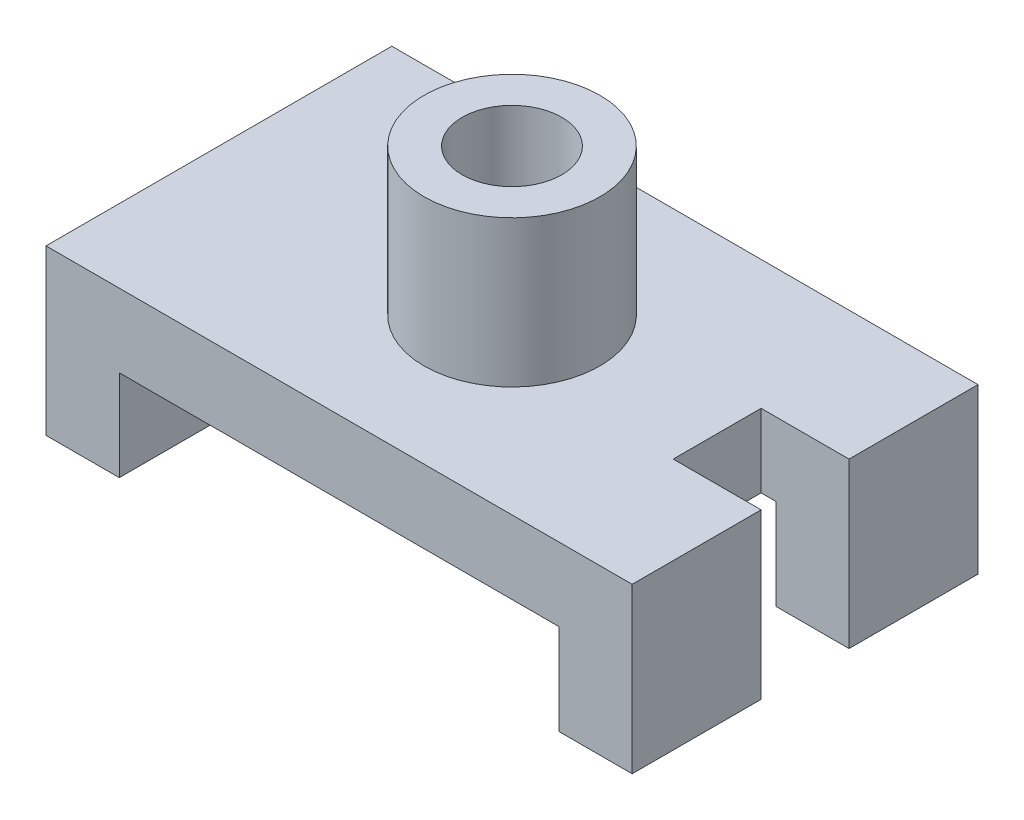
SolidWorks part; units mm, degrees
ref_plane "Alzado" through (0, 0, 0) normal (0, 0, 1) x (1, 0, 0)
ref_plane "Planta" through (0, 0, 0) normal (0, 1, 0) x (1, 0, 0)
ref_plane "Vista lateral" through (0, 0, 0) normal (1, 0, 0) x (0, 0, -1)
sketch "Croquis1" plane through (0, 0, 0) normal (0, 0, 1) x (1, 0, 0)
  line L0 (-3.5, 0) -> (-4, 0)
  line L1 (0, 0) -> (-0.5, 0)
  line L2 (0, 0) -> (0, 1.12)
  line L3 (0, 1.12) -> (-4, 1.12)
  line L4 (-4, 0) -> (-4, 1.12)
  line L6 (-3.5, 0) -> (-3.5, 0.62)
  line L7 (-3.5, 0.62) -> (-0.5, 0.62)
  line L8 (-0.5, 0) -> (-0.5, 0.62)
  dimension "D1" = 3
  dimension "D2" = 4
  dimension "D3" = 1.12
  dimension "D4" = 0.5
extrude "Saliente-Extruir2" add sketch "Croquis1" along normal mid plane 2.36
sketch "Croquis2" plane through (0, 1.12, 0) normal (0, 1, 0) x (1, 0, 0)
  line L0 (0, -1.18) -> (0, 1.18) construction
  line L1 (0, 0.3) -> (-0.6, 0.3)
  line L2 (0, 0.3) -> (0, -0.3)
  line L3 (0, -0.3) -> (-0.6, -0.3)
  line L4 (-0.6, 0.3) -> (-0.6, -0.3)
  line L5 (0, 1.18) -> (-4, 1.18) construction
  dimension "D1" = 0.6
  dimension "D2" = 0.6
  dimension "D3" = 0.88
extrude "Cortar-Extruir1" cut sketch "Croquis2" against normal through all
sketch "Croquis3" plane through (0, 1.12, 0) normal (0, 1, 0) x (1, 0, 0)
  line L0 (0, -1.18) -> (-4, -1.18) construction
  circle A0 centre (-2, 0) radius 0.6
  circle A1 centre (-2, 0) radius 0.34
  point P8 (-2, -1.18)
  dimension "D1" = 1.2
  dimension "D2" = 0.68
extrude "Saliente-Extruir3" add sketch "Croquis3" along normal blind 1
